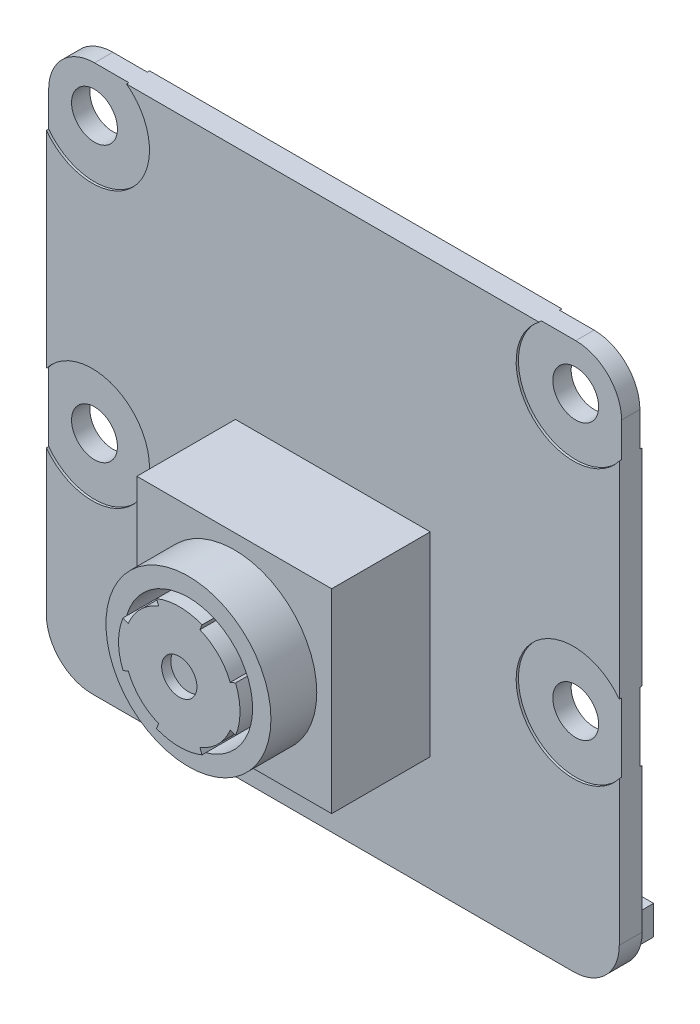
SolidWorks part; units mm, degrees
ref_plane "前视基准面" through (0, 0, 0) normal (0, 0, 1) x (1, 0, 0)
ref_plane "上视基准面" through (0, 0, 0) normal (0, 1, 0) x (1, 0, 0)
ref_plane "右视基准面" through (0, 0, 0) normal (1, 0, 0) x (0, 0, -1)
sketch "草图1" plane through (0, 0, 0) normal (0, 0, 1) x (1, 0, 0)
  line L0 (12.5, 28.4307) -> (12.5, -8.3496) construction
  line L1 (2, 0) -> (23, 0)
  line L2 (0, 2) -> (0, 21.8)
  line L3 (2, 23.8) -> (23, 23.8)
  line L4 (25, 2) -> (25, 21.8)
  arc A0 (0, 21.8) -> (2, 23.8) centre (2, 21.8) cw
  arc A1 (2, 0) -> (0, 2) centre (2, 2) cw
  arc A2 (23, 0) -> (25, 2) centre (23, 2) ccw
  arc A3 (25, 21.8) -> (23, 23.8) centre (23, 21.8) ccw
  circle A4 centre (23, 21.8) radius 1
  circle A5 centre (2, 21.8) radius 1
  circle A6 centre (2, 9.8) radius 1
  circle A7 centre (23, 9.8) radius 1
  point P7 (0, 23.8)
  point P10 (0, 0)
  point P13 (25, 0)
  point P16 (25, 23.8)
  dimension "D3" = 2
  dimension "D4" = 2
  dimension "D1" = 23.8
  dimension "D2" = 25
  dimension "D5" = 2
  dimension "D6" = 2
extrude "凸台-拉伸1" add sketch "草图1" along normal blind 1
sketch "草图6" plane through (0, 0, 1) normal (0, 0, 1) x (1, 0, 0)
  line L0 (25, 20.3) -> (25, 21.8)
  line L1 (0, 11.3) -> (0, 8.3)
  line L2 (3.5, 23.8) -> (2, 23.8)
  line L4 (0, 21.8) -> (0, 2)
  line L5 (2, 0) -> (23, 0)
  line L6 (25, 2) -> (25, 21.8)
  line L7 (23, 23.8) -> (2, 23.8)
  line L8 (0, 21.8) -> (0, 20.3)
  line L10 (25, 8.3) -> (25, 11.3)
  line L11 (23, 23.8) -> (21.5, 23.8)
  arc A0 (0, 20.3) -> (3.5, 23.8) centre (2, 21.8) ccw
  arc A1 (21.5, 23.8) -> (25, 20.3) centre (23, 21.8) ccw
  arc A2 (25, 11.3) -> (25, 8.3) centre (23, 9.8) ccw
  arc A3 (0, 8.3) -> (0, 11.3) centre (2, 9.8) ccw
  arc A8 (2, 23.8) -> (0, 21.8) centre (2, 21.8) ccw
  arc A9 (0, 2) -> (2, 0) centre (2, 2) ccw
  arc A10 (23, 0) -> (25, 2) centre (23, 2) ccw
  arc A11 (25, 21.8) -> (23, 23.8) centre (23, 21.8) ccw
  arc A12 (2, 23.8) -> (0, 21.8) centre (2, 21.8) ccw
  arc A15 (25, 21.8) -> (23, 23.8) centre (23, 21.8) ccw
  dimension "D1" = 5
  dimension "D2" = 0
extrude "切除-拉伸1" cut sketch "草图6" against normal blind 0.1
sketch "草图7" plane through (0, 0, 0) normal (0, 0, -1) x (-1, 0, 0)
  line L0 (-3.5, 23.8) -> (-2, 23.8) construction
  line L1 (0, 21.8) -> (0, 20.3) construction
  line L2 (0, 11.3) -> (0, 8.3) construction
  line L3 (-25, 8.3) -> (-25, 11.3) construction
  line L4 (-23, 23.8) -> (-21.5, 23.8) construction
  line L5 (-25, 20.3) -> (-25, 21.8) construction
  line L6 (-3.5, 23.8) -> (-2, 23.8)
  line L7 (0, 21.8) -> (0, 20.3)
  line L8 (0, 11.3) -> (0, 8.3)
  line L9 (-25, 8.3) -> (-25, 11.3)
  line L10 (-23, 23.8) -> (-21.5, 23.8)
  line L11 (-25, 20.3) -> (-25, 21.8)
  arc A0 (0, 21.8) -> (-2, 23.8) centre (-2, 21.8) ccw construction
  arc A1 (-3.5, 23.8) -> (0, 20.3) centre (-2, 21.8) ccw construction
  arc A2 (0, 11.3) -> (0, 8.3) centre (-2, 9.8) ccw construction
  arc A3 (-25, 8.3) -> (-25, 11.3) centre (-23, 9.8) ccw construction
  arc A4 (-23, 23.8) -> (-25, 21.8) centre (-23, 21.8) ccw construction
  arc A5 (-25, 20.3) -> (-21.5, 23.8) centre (-23, 21.8) ccw construction
  arc A6 (0, 21.8) -> (-2, 23.8) centre (-2, 21.8) ccw
  arc A7 (-3.5, 23.8) -> (0, 20.3) centre (-2, 21.8) ccw
  arc A8 (0, 11.3) -> (0, 8.3) centre (-2, 9.8) ccw
  arc A9 (-25, 8.3) -> (-25, 11.3) centre (-23, 9.8) ccw
  arc A10 (-23, 23.8) -> (-25, 21.8) centre (-23, 21.8) ccw
  arc A11 (-25, 20.3) -> (-21.5, 23.8) centre (-23, 21.8) ccw
  point P0 (0, 8.3)
extrude "切除-拉伸2" cut sketch "草图7" against normal blind 0.1
sketch "草图2" plane through (0, 0, 1) normal (0, 0, 1) x (1, 0, 0)
  line L0 (2, 0) -> (23, 0) construction
  line L1 (8.25, 13.5) -> (16.75, 13.5)
  line L2 (8.25, 13.5) -> (8.25, 5)
  line L3 (8.25, 5) -> (16.75, 5)
  line L4 (16.75, 13.5) -> (16.75, 5)
  line L5 (12.5, -1.8712) -> (12.5, 24.7318) construction
  point P8 (12.5, 0)
  dimension "D1" = 5
  dimension "D2" = 8.5
extrude "凸台-拉伸2" add sketch "草图2" along normal blind 4.3
sketch "草图3" plane through (0, 0, 5.3) normal (0, 0, 1) x (1, 0, 0)
  line L1 (8.25, 13.5) -> (8.25, 5) construction
  line L2 (16.75, 13.5) -> (8.25, 13.5) construction
  circle A0 centre (12.5, 9.25) radius 3.6
  circle A1 centre (12.5, 9.25) radius 2.8
  point P4 (8.25, 9.25)
  point P7 (12.5, 13.5)
  dimension "D1" = 7.2
  dimension "D2" = 5.6
extrude "凸台-拉伸3" add sketch "草图3" along normal blind 2
sketch "草图4" plane through (0, 0, 5.3) normal (0, 0, 1) x (1, 0, 0)
  line L0 (11.5062, 11.7066) -> (11.6, 11.4749)
  line L1 (13.4, 11.4749) -> (13.4937, 11.7066)
  line L2 (12.5, 10.9455) -> (12.5, 12.6452) construction
  line L3 (14.7249, 8.35) -> (14.9566, 8.2563)
  line L4 (14.9566, 10.2438) -> (14.7249, 10.15)
  line L5 (11.6, 7.0251) -> (11.5062, 6.7934)
  line L6 (13.4938, 6.7934) -> (13.4, 7.0251)
  line L7 (10.2751, 10.15) -> (10.0434, 10.2438)
  line L8 (10.0434, 8.2563) -> (10.2751, 8.35)
  arc A0 (10.0434, 10.2438) -> (10.0434, 8.2563) centre (12.5, 9.25) ccw
  circle A1 centre (12.5, 9.25) radius 0.77
  arc A2 (10.2751, 8.35) -> (11.6, 7.0251) centre (12.5, 9.25) ccw
  arc A3 (13.4, 7.0251) -> (14.7249, 8.35) centre (12.5, 9.25) ccw
  arc A4 (14.7249, 10.15) -> (13.4, 11.4749) centre (12.5, 9.25) ccw
  arc A5 (11.6, 11.4749) -> (10.2751, 10.15) centre (12.5, 9.25) ccw
  arc A6 (11.5062, 6.7934) -> (13.4938, 6.7934) centre (12.5, 9.25) ccw
  arc A7 (14.9566, 8.2563) -> (14.9566, 10.2438) centre (12.5, 9.25) ccw
  arc A8 (13.4937, 11.7066) -> (11.5062, 11.7066) centre (12.5, 9.25) ccw
  point P26 (12.5, 9.25)
  dimension "D1" = 5.3
  dimension "D2" = 1.54
  dimension "D3" = 4.8
  dimension "D4" = 1.8
  dimension "D5" = 4
extrude "凸台-拉伸4" add sketch "草图4" along normal blind 2.4
sketch "草图5" plane through (0, 0, 5.3) normal (0, 0, 1) x (1, 0, 0)
  line L0 (-4.0283, 9.25) -> (28.8005, 9.25) construction
  circle A1 centre (12.5, 9.25) radius 0.77
  circle A2 centre (12.5, 9.25) radius 0.77
  dimension "D1" = 0
extrude "凸台-拉伸5" add sketch "草图5" along normal blind 2
sketch "草图8" plane through (0, 0, 0) normal (0, 0, -1) x (-1, 0, 0)
  line L0 (-2, 0) -> (-23, 0) construction
  line L1 (-23.5, 0) -> (-1.5, 0)
  line L2 (-23.5, 0) -> (-23.5, 1.3356)
  line L3 (-22.75, 5) -> (-2.25, 5)
  line L4 (-1.5, 0) -> (-1.5, 1.3356)
  line L5 (-12.5, 24.5311) -> (-12.5, -5.7528) construction
  line L6 (-21.5, 23.8) -> (-3.5, 23.8) construction
  line L7 (-22.75, 1.3356) -> (-23.5, 1.3356)
  line L8 (-22.75, 5) -> (-2.25, 5)
  line L9 (-22.75, 5) -> (-22.75, 1.3356)
  line L11 (-2.25, 5) -> (-2.25, 1.3356)
  line L12 (-2.25, 1.3356) -> (-1.5, 1.3356)
  point P10 (-12.5, 23.8)
  arc M14 (-25, 2) -> (-23, 0) centre (-23, 2) ccw
  line M15 (-23, 0) -> (-2, 0)
  arc M16 (-2, 0) -> (0, 2) centre (-2, 2) ccw
  dimension "D2" = 22
  dimension "D4" = 20.5
extrude "凸台-拉伸6" add sketch "草图8" along normal blind 2 separate body contours L5 L3 L9 L7 L2 M14 M15 | L8 L5 L1 L4 L12 L11 M16
ref_plane "基准面1" through (0, 9.25, 0) normal (0, 1, 0) x (1, 0, 0)
